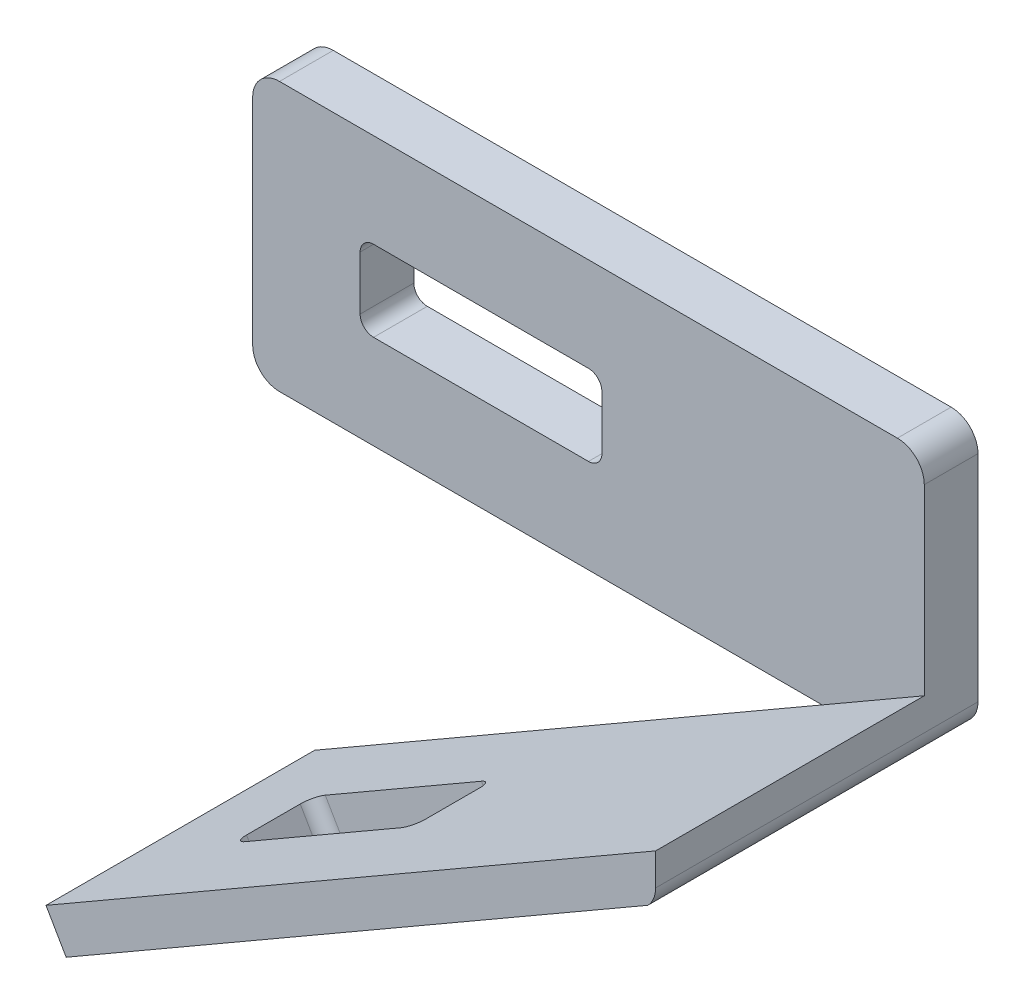
SolidWorks part; units mm, degrees
ref_plane "Plan de face" through (0, 0, 0) normal (0, 0, 1) x (1, 0, 0)
ref_plane "Plan de dessus" through (0, 0, 0) normal (0, 1, 0) x (1, 0, 0)
ref_plane "Plan de droite" through (0, 0, 0) normal (1, 0, 0) x (0, 0, -1)
sketch "Esquisse1" plane through (0, 0, 0) normal (0, 0, 1) x (1, 0, 0)
  line L1 (-11.2733, 8.7087) -> (34.7267, 8.7087)
  line L2 (-13.2733, 6.7087) -> (-13.2733, -9.2913)
  line L3 (-11.2733, -11.2913) -> (34.7267, -11.2913)
  line L4 (36.7267, 6.7087) -> (36.7267, -9.2913)
  arc A0 (34.7267, 8.7087) -> (36.7267, 6.7087) centre (34.7267, 6.7087) cw
  arc A1 (36.7267, -9.2913) -> (34.7267, -11.2913) centre (34.7267, -9.2913) cw
  arc A2 (-11.2733, -11.2913) -> (-13.2733, -9.2913) centre (-11.2733, -9.2913) cw
  arc A3 (-13.2733, 6.7087) -> (-11.2733, 8.7087) centre (-11.2733, 6.7087) cw
  point P8 (36.7267, -11.2913)
  point P11 (-13.2733, -11.2913)
  point P14 (-13.2733, 8.7087)
  dimension "D3" = 2
  dimension "D1" = 20
  dimension "D2" = 50
extrude "Boss.-Extru.1" add sketch "Esquisse1" along normal blind 4
sketch "Esquisse2" plane through (0, 0, 4) normal (0, 0, 1) x (1, 0, 0)
  line L1 (31.7267, 8.7087) -> (34.7267, 8.7087)
  line L2 (31.7267, 8.7087) -> (31.7267, -11.2913)
  line L3 (31.7267, -11.2913) -> (34.7267, -11.2913)
  line L4 (36.7267, 6.7087) -> (36.7267, -9.2913)
  line L5 (36.7267, -9.2913) -> (36.7267, 6.7087) construction
  line L6 (34.7267, 8.7087) -> (-11.2733, 8.7087) construction
  line L7 (-11.2733, -11.2913) -> (34.7267, -11.2913) construction
  arc A0 (34.7267, 8.7087) -> (36.7267, 6.7087) centre (34.7267, 6.7087) cw
  arc A1 (36.7267, -9.2913) -> (34.7267, -11.2913) centre (34.7267, -9.2913) cw
  dimension "D1" = 2
  dimension "D2" = 3
sketch "Esquisse3" plane through (0, 0, 4) normal (0, 0, 1) x (1, 0, 0)
  line L0 (-13.2733, 6.7087) -> (-13.2733, -9.2913) construction
  line L1 (-4.2733, 1.7087) -> (11.7267, 1.7087)
  line L2 (-5.2733, 0.7087) -> (-5.2733, -3.2913)
  line L3 (-4.2733, -4.2913) -> (11.7267, -4.2913)
  line L4 (12.7267, 0.7087) -> (12.7267, -3.2913)
  line L5 (-5.2733, 1.7087) -> (12.7267, -4.2913) construction
  line L6 (-5.2733, -4.2913) -> (12.7267, 1.7087) construction
  line L7 (-11.2733, -11.2913) -> (34.7267, -11.2913) construction
  line L8 (34.7267, 8.7087) -> (-11.2733, 8.7087) construction
  arc A0 (-5.2733, 0.7087) -> (-4.2733, 1.7087) centre (-4.2733, 0.7087) cw
  arc A1 (-5.2733, -3.2913) -> (-4.2733, -4.2913) centre (-4.2733, -3.2913) ccw
  arc A2 (11.7267, -4.2913) -> (12.7267, -3.2913) centre (11.7267, -3.2913) ccw
  arc A3 (12.7267, 0.7087) -> (11.7267, 1.7087) centre (11.7267, 0.7087) ccw
  point P0 (3.7267, -1.2913)
  dimension "D4" = 1
  dimension "D1" = 18
  dimension "D2" = 6
  dimension "D3" = 8
  dimension "D5" = 7
  dimension "D6" = 7
extrude "Enlèv. mat.-Extru.1" cut sketch "Esquisse3" against normal blind 50
sketch "Esquisse4" plane through (0, 0, 4) normal (0, 0, 1) x (1, 0, 0)
  line L1 (36.1417, -10.7047) -> (-7.1594, -35.7049)
  line L2 (36.7267, 6.7087) -> (36.7267, -9.2913) construction
  line L9 (-7.1594, -35.7049) -> (-8.6594, -33.1068)
  line L10 (-8.6594, -33.1068) -> (36.7267, -6.9028)
  line L11 (-11.2733, -11.2913) -> (34.7267, -11.2913) construction
  line L17 (36.7267, -6.9028) -> (36.7267, -9.2913)
  arc A1 (36.7267, -9.2913) -> (36.1417, -10.7047) centre (34.7267, -9.2913) cw
  point P5 (0, 0)
  point P6 (0, 0)
  point P8 (0, 0)
  point P12 (0, 0)
  dimension "D1" = 30
  dimension "D2" = 3
extrude "Boss.-Extru.2" add sketch "Esquisse4" along normal blind 20
sketch "Esquisse5" plane through (12.1709, -21.0803, 0) normal (-0.5, 0.866, 0) x (0.866, 0.5, 0)
  line L0 (-24.0528, -24) -> (-24.0528, -4) construction
  line L1 (-15.0528, -11) -> (-1.6326, -11)
  line L2 (-16.0528, -12) -> (-16.0528, -16)
  line L3 (-15.0528, -17) -> (-1.6326, -17)
  line L4 (-0.6326, -12) -> (-0.6326, -16)
  line L5 (-16.0528, -11) -> (-0.6326, -17) construction
  line L6 (-16.0528, -17) -> (-0.6326, -11) construction
  line L7 (19.5779, -4) -> (-24.0528, -4) construction
  line L8 (28.3547, -24) -> (-24.0528, -24) construction
  arc A0 (-15.0528, -11) -> (-16.0528, -12) centre (-15.0528, -12) ccw
  arc A1 (-16.0528, -16) -> (-15.0528, -17) centre (-15.0528, -16) ccw
  arc A2 (-1.6326, -11) -> (-0.6326, -12) centre (-1.6326, -12) cw
  arc A3 (-1.6326, -17) -> (-0.6326, -16) centre (-1.6326, -16) ccw
  point P0 (-8.3427, -14)
  dimension "D4" = 1
  dimension "D5" = 1
  dimension "D6" = 1
  dimension "D7" = 1
  dimension "D1" = 8
  dimension "D2" = 7
  dimension "D3" = 7
extrude "Enlèv. mat.-Extru.2" cut sketch "Esquisse5" against normal up to next
